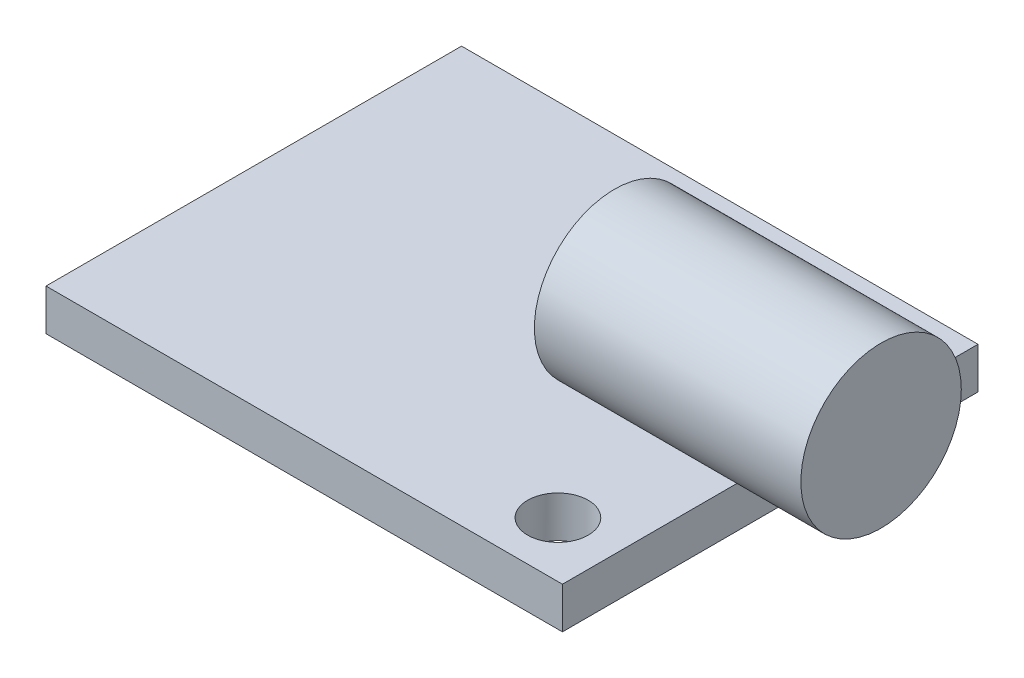
SolidWorks part; units mm, degrees
ref_plane "Front Plane" through (0, 0, 0) normal (0, 0, 1) x (1, 0, 0)
ref_plane "Top Plane" through (0, 0, 0) normal (0, 1, 0) x (1, 0, 0)
ref_plane "Right Plane" through (0, 0, 0) normal (1, 0, 0) x (0, 0, -1)
sketch "Sketch1" plane through (0, 0, 0) normal (0, 1, 0) x (1, 0, 0)
  line L1 (0, 0) -> (19.05, 0)
  line L2 (0, 0) -> (0, -15.3289)
  line L3 (0, -15.3289) -> (19.05, -15.3289)
  line L4 (19.05, 0) -> (19.05, -15.3289)
  dimension "D1" = 19.05
  dimension "D2" = 15.3289
extrude "Boss-Extrude1" add sketch "Sketch1" along normal blind 1.524 contours L2 L1 L4 L3
sketch "Sketch3" plane through (19.05, 0, 0) normal (1, 0, 0) x (0, 0, -1)
  circle A0 centre (-7.6645, 4.4831) radius 2.9591
extrude "Boss-Extrude2" add sketch "Sketch3" along normal blind 4.0894 and the other way blind 5.7404 separate body
sketch "Sketch6" plane through (0, 1.524, 0) normal (0, 1, 0) x (1, 0, 0)
  circle A0 centre (16.8424, -13.2872) radius 1.1176
  circle A1 centre (16.8424, -2.7843) radius 1.1176
  dimension "D1" = 2.2352
  dimension "D4" = 2.2352
  dimension "D5" = 10.5029
extrude "Cut-Extrude1" cut sketch "Sketch6" against normal blind 4.0894
